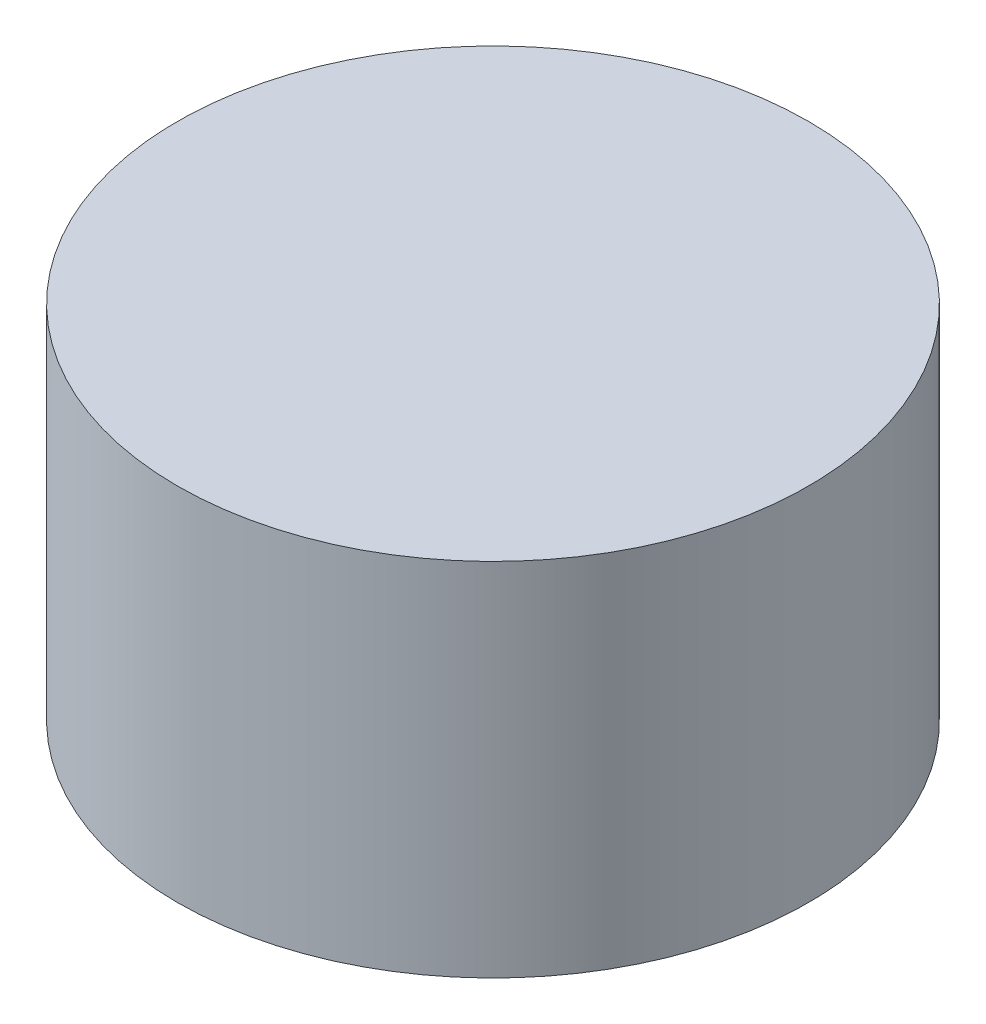
SolidWorks part; units mm, degrees
material "6061-T6 (SS)"
ref_plane "Front Plane" through (0, 0, 0) normal (0, 0, 1) x (1, 0, 0)
ref_plane "Top Plane" through (0, 0, 0) normal (0, 1, 0) x (1, 0, 0)
ref_plane "Right Plane" through (0, 0, 0) normal (1, 0, 0) x (0, 0, -1)
sketch "Sketch2" plane through (0, 0, 0) normal (0, 0, 1) x (1, 0, 0)
  line L0 (0, 0) -> (0, 27.9105) construction
  line L1 (0, 0) -> (-22.225, 0)
  line L2 (-22.225, 0) -> (-22.225, 25.4)
  line L3 (-22.225, 25.4) -> (0, 25.4)
  line L4 (0, 25.4) -> (0, 0)
  point P3 (0, 27.9105)
  dimension "D1" = 44.45
  dimension "D2" = 25.4
revolve "Body" add sketch "Sketch2" angle 360 about L0
